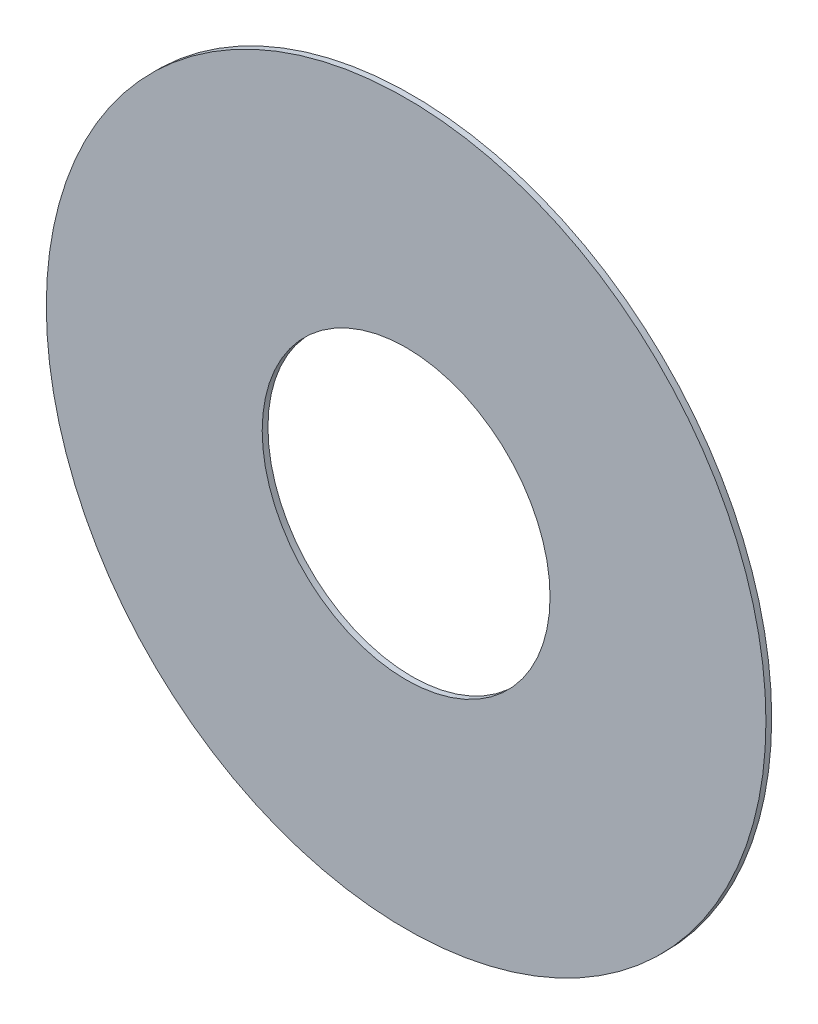
SolidWorks part; units mm, degrees
ref_plane "Front Plane" through (0, 0, 0) normal (0, 0, 1) x (1, 0, 0)
ref_plane "Top Plane" through (0, 0, 0) normal (0, 1, 0) x (1, 0, 0)
ref_plane "Right Plane" through (0, 0, 0) normal (1, 0, 0) x (0, 0, -1)
sketch "Sketch1" plane through (0, 0, 0) normal (0, 0, 1) x (1, 0, 0)
  circle A0 centre (0, 0) radius 5
  circle A1 centre (0, 0) radius 12.5
  dimension "D1" = 10
  dimension "D2" = 25
extrude "Boss-Extrude2" add sketch "Sketch1" along normal blind 0.2
scale "Scale1" scale about centroid uniform scaling yes scale factor 1.9329
scale "Scale2" scale about centroid uniform scaling yes scale factor 1.5
